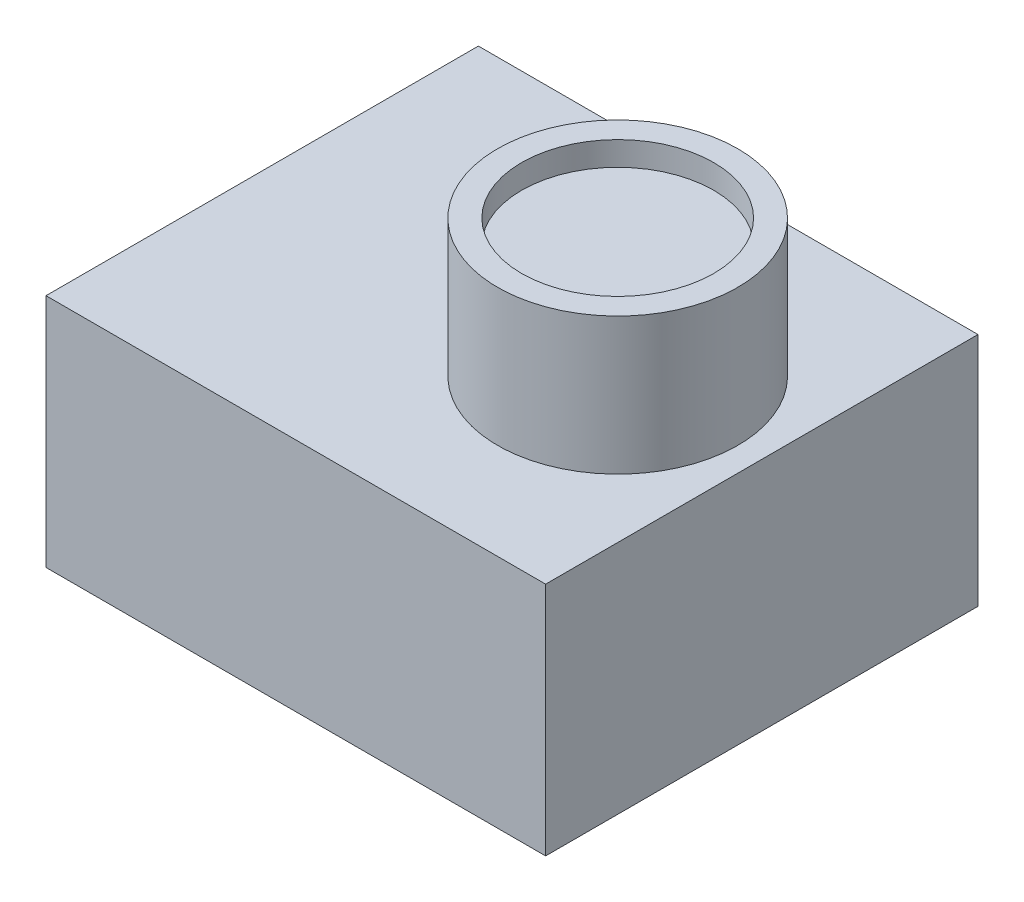
SolidWorks part; units mm, degrees
ref_plane "Front Plane" through (0, 0, 0) normal (0, 0, 1) x (1, 0, 0)
ref_plane "Top Plane" through (0, 0, 0) normal (0, 1, 0) x (1, 0, 0)
ref_plane "Right Plane" through (0, 0, 0) normal (1, 0, 0) x (0, 0, -1)
sketch "Sketch1" plane through (0, 0, 0) normal (0, 1, 0) x (1, 0, 0)
  line L1 (-104, -90) -> (104, -90)
  line L2 (-104, -90) -> (-104, 90)
  line L3 (-104, 90) -> (104, 90)
  line L4 (104, -90) -> (104, 90)
  line L5 (-104, -90) -> (104, 90) construction
  line L6 (-104, 90) -> (104, -90) construction
  point P0 (0, 0)
  dimension "D1" = 208
  dimension "D2" = 180
extrude "Boss-Extrude1" add sketch "Sketch1" along normal blind 98
sketch "Sketch2" plane through (0, 98, 0) normal (0, 1, 0) x (1, 0, 0)
  line L0 (104, -90) -> (104, 90) construction
  circle A0 centre (44, 0) radius 50
  dimension "D1" = 100
  dimension "D2" = 60
extrude "Boss-Extrude2" add sketch "Sketch2" along normal blind 57
sketch "Sketch3" plane through (0, 155, 0) normal (0, 1, 0) x (1, 0, 0)
  circle A0 centre (44, 0) radius 40
extrude "Cut-Extrude1" cut sketch "Sketch3" against normal blind 10
